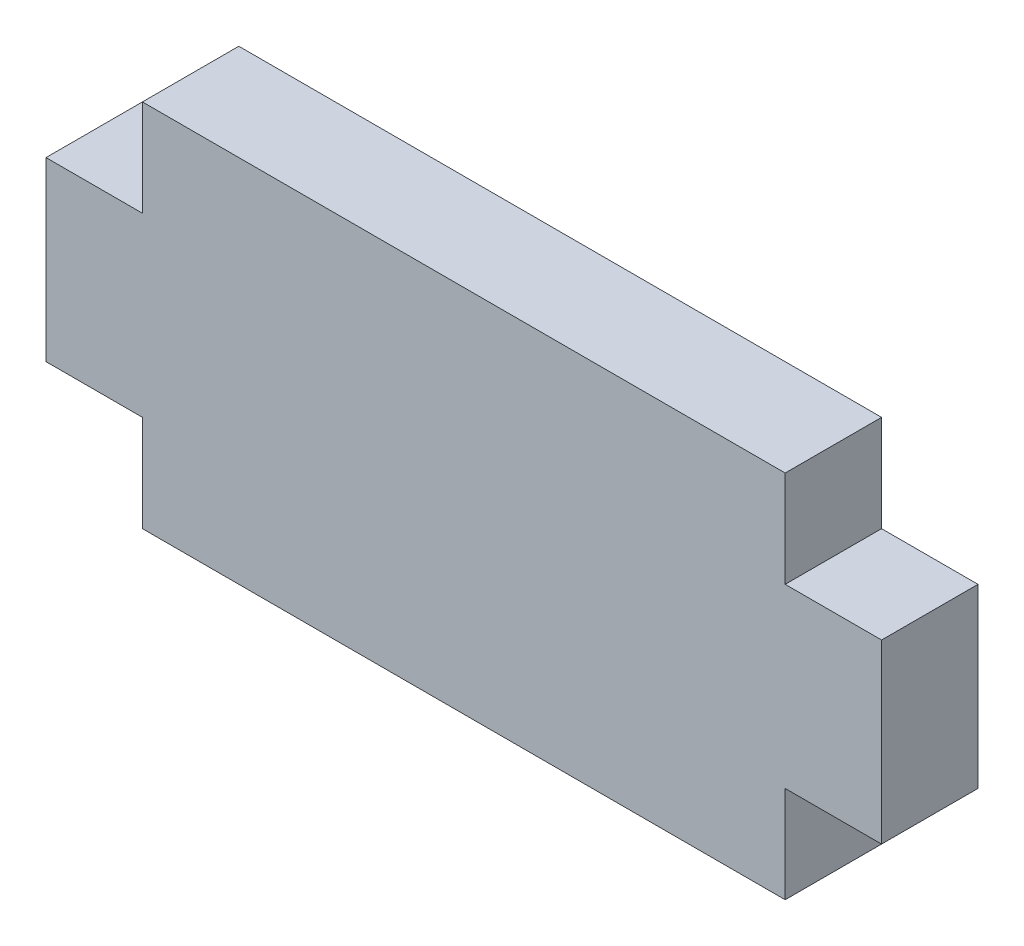
SolidWorks part; units mm, degrees
material "Plywood"
ref_plane "Plan de face" through (0, 0, 0) normal (0, 0, 1) x (1, 0, 0)
ref_plane "Plan de dessus" through (0, 0, 0) normal (0, 1, 0) x (1, 0, 0)
ref_plane "Plan de droite" through (0, 0, 0) normal (1, 0, 0) x (0, 0, -1)
sketch "Esquisse1" plane through (0, 0, 0) normal (0, 0, 1) x (1, 0, 0)
  line L1 (0, 0) -> (52, 0)
  line L2 (0, 0) -> (0, 23)
  line L3 (0, 23) -> (52, 23)
  line L4 (52, 0) -> (52, 23)
  dimension "D1" = 23
  dimension "D2" = 52
extrude "Boss.-Extru.1" add sketch "Esquisse1" along normal blind 6
sketch "Esquisse2" plane through (0, 0, 6) normal (0, 0, 1) x (1, 0, 0)
  line L1 (0, 23) -> (6, 23)
  line L2 (0, 23) -> (0, 17)
  line L3 (0, 17) -> (6, 17)
  line L4 (6, 23) -> (6, 17)
  line L6 (0, 23) -> (0, 0) construction
  line L7 (26, 6.9967) -> (26, 19.8492) construction
  line L9 (52, 11.5) -> (-6.8556, 11.5) construction
  line L10 (52, 0) -> (52, 23) construction
  line L11 (6, 0) -> (6, 6)
  line L12 (0, 6) -> (6, 6)
  line L13 (0, 0) -> (0, 6)
  line L14 (0, 0) -> (6, 0)
  line L15 (52, 0) -> (52, 6)
  line L16 (52, 6) -> (46, 6)
  line L17 (46, 0) -> (46, 6)
  line L18 (52, 0) -> (46, 0)
  line L19 (46, 23) -> (46, 17)
  line L20 (52, 17) -> (46, 17)
  line L21 (52, 23) -> (52, 17)
  line L22 (52, 23) -> (46, 23)
  point P27 (0, 0)
  dimension "D2" = 6
  dimension "D3" = 6
extrude "Enlèv. mat.-Extru.1" cut sketch "Esquisse2" against normal blind 10
